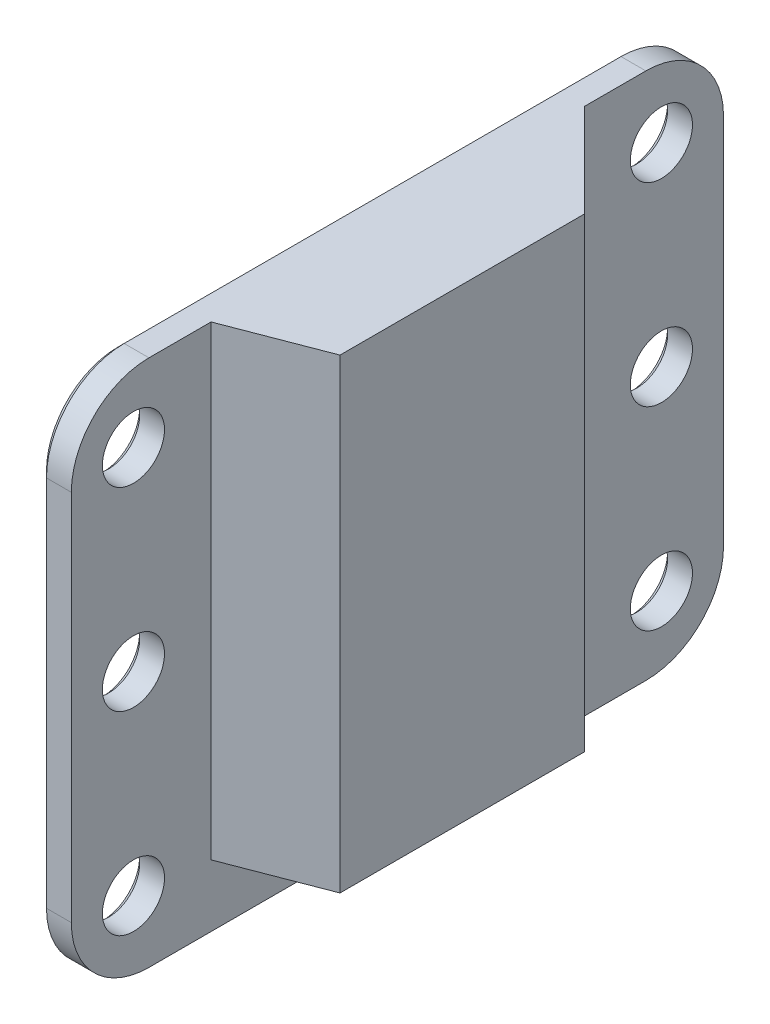
SolidWorks part; units mm, degrees
ref_plane "Спереди" through (0, 0, 0) normal (0, 0, 1) x (1, 0, 0)
ref_plane "Сверху" through (0, 0, 0) normal (0, 1, 0) x (1, 0, 0)
ref_plane "Справа" through (0, 0, 0) normal (1, 0, 0) x (0, 0, -1)
sketch "Эскиз1" plane through (0, 0, 0) normal (1, 0, 0) x (0, 0, -1)
  line L0 (8.5, 0.5901) -> (8.5, 50000.5901) construction
  line L1 (-8, -8.5) -> (8, -8.5)
  line L2 (-10.5, -6) -> (-10.5, 6)
  line L3 (-8, 8.5) -> (8, 8.5)
  line L4 (10.5, -6) -> (10.5, 6)
  line L5 (-10.5, -8.5) -> (10.5, 8.5) construction
  line L6 (-10.5, 8.5) -> (10.5, -8.5) construction
  circle A0 centre (8.5, 6.25) radius 1
  circle A1 centre (-8.5, 6.25) radius 1
  circle A2 centre (-8.5, 0) radius 1
  circle A3 centre (-8.5, -6.25) radius 1
  circle A4 centre (8.5, 0) radius 1
  circle A5 centre (8.5, -6.25) radius 1
  arc A6 (8, 8.5) -> (10.5, 6) centre (8, 6) cw
  arc A7 (-10.5, 6) -> (-8, 8.5) centre (-8, 6) cw
  arc A8 (-10.5, -6) -> (-8, -8.5) centre (-8, -6) ccw
  arc A9 (8, -8.5) -> (10.5, -6) centre (8, -6) ccw
  point P0 (0, 0)
  dimension "D5" = 2
  dimension "D10" = 2.5
  dimension "D12" = 2
  dimension "D13" = 2
  dimension "D14" = 2.5
  dimension "D1" = 21
  dimension "D2" = 17
  dimension "D3" = 8.5
  dimension "D4" = 2.25
  dimension "D8" = 6.25
  dimension "D9" = 17
  dimension "D11" = 8.5
  dimension "D6" = 2
  dimension "D7" = 3
extrude "Бобышка-Вытянуть1" add sketch "Эскиз1" along normal blind 1
chamfer "Фаска1" distance 0.2 angle 45 14 edges at (0, -6.25, -9.5) (0, -6.25, 7.5) (0, 6.25, 7.5) (0, 8.5, 0) (0, 7.7678, 9.7678) (0, 0, 10.5) (0, -7.7678, 9.7678) (0, -8.5, 0) (0, -7.7678, -9.7678) (0, 0, -10.5) (0, 7.7678, -9.7678) (0, 6.25, -9.5) (0, 0, 7.5) (0, 0, -9.5)
sketch "Эскиз4" plane through (0, 0, 0) normal (-1, 0, 0) x (0, 0, 1)
  text T0 "СПбПУ\r\n" font "Arial" height in points 9
  text T1 "3331506/60401" font "Arial" height in points 6
extrude "Вырез-Вытянуть1" cut sketch "Эскиз4" against normal blind 0.1
sketch "Эскиз5" plane through (0, -8.5, 0) normal (0, -1, 0) x (1, 0, 0)
  line L0 (1, -6.0207) -> (4, -3.0207)
  line L1 (1, 8) -> (1, -8) construction
  line L2 (4, -7.5485) -> (4, 49992.4515) construction
  line L4 (1, -6.0207) -> (1, 6)
  line L5 (1, 6) -> (4, 4.8484)
  line L6 (0, -8) -> (0, 8) construction
  line L7 (4, -3.0207) -> (4, 4.8484)
  point P8 (0, 0)
  dimension "D1" = 6
  dimension "D2" = 45
  dimension "D3" = 69
  dimension "D4" = 4
  dimension "D5" = 6
extrude "Бобышка-Вытянуть3" add sketch "Эскиз5" against normal blind 15 from offset 2
